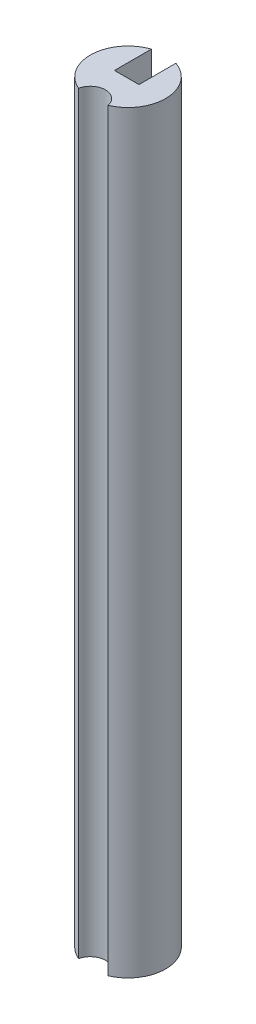
SolidWorks part; units mm, degrees
material "ABS"
ref_plane "Plano frontal" through (0, 0, 0) normal (0, 0, 1) x (1, 0, 0)
ref_plane "Plano superior" through (0, 0, 0) normal (0, 1, 0) x (1, 0, 0)
ref_plane "Plano direito" through (0, 0, 0) normal (1, 0, 0) x (0, 0, -1)
sketch "Esboço1" plane through (0, 0, 0) normal (0, 1, 0) x (1, 0, 0)
  line L13 (-3.25, -0.3429) -> (3.25, -0.3429)
  line L14 (-3.25, -0.3429) -> (-3.25, 9.4571)
  line L16 (3.25, -0.3429) -> (3.25, 9.4571)
  arc A5 (-3.25, 9.4571) -> (-3.9192, -9.2) centre (0, 0) ccw
  arc A6 (3.9192, -9.2) -> (-3.9192, -9.2) centre (0, -10) ccw
  arc A7 (3.9192, -9.2) -> (3.25, 9.4571) centre (0, 0) ccw
  dimension "D1" = 9.8
  dimension "D2" = 10
extrude "Ressalto-extrusão1" add sketch "Esboço1" along normal blind 200
